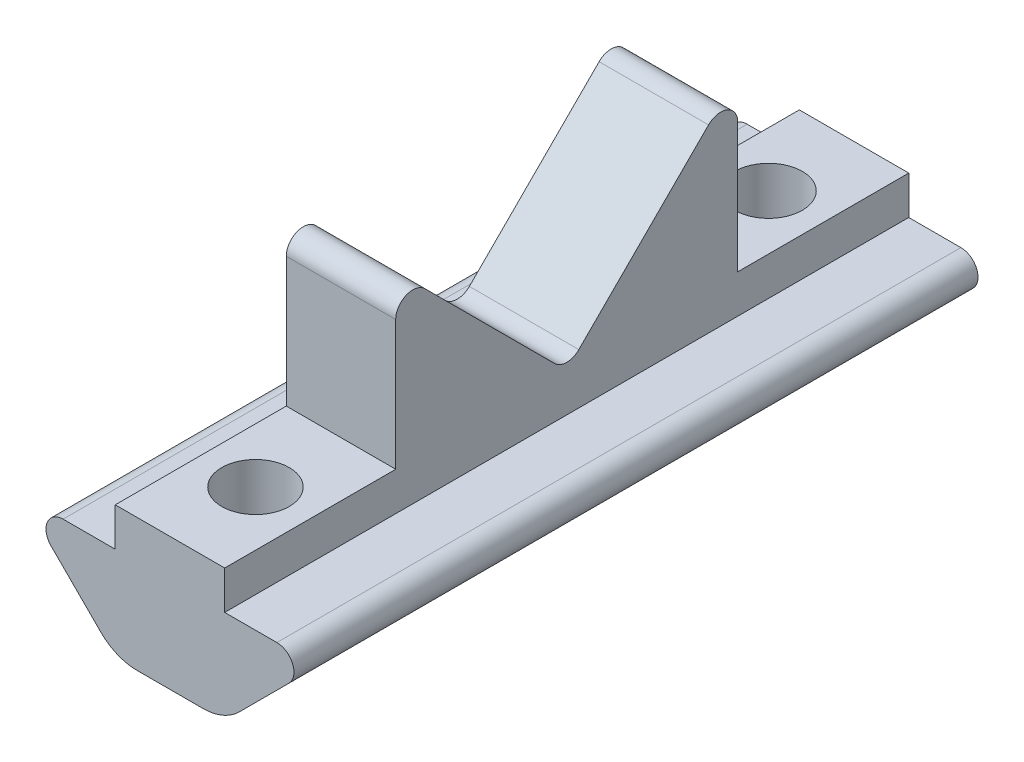
SolidWorks part; units mm, degrees
material "PETG"
ref_plane "Front Plane" through (0, 0, 0) normal (0, 0, 1) x (1, 0, 0)
ref_plane "Top Plane" through (0, 0, 0) normal (0, 1, 0) x (1, 0, 0)
ref_plane "Right Plane" through (0, 0, 0) normal (1, 0, 0) x (0, 0, -1)
sketch "Sketch2" plane through (0, 0, 0) normal (0, 0, 1) x (1, 0, 0)
  line L0 (-1.9216, 0) -> (1.9216, 0)
  line L1 (4.0429, 0.8787) -> (6.9571, 3.7929)
  line L2 (6.25, 5.5) -> (3.2, 5.5)
  line L3 (3.2, 5.5) -> (3.2, 7.75)
  line L4 (3.2, 7.75) -> (-3.2, 7.75)
  line L5 (-3.2, 7.75) -> (-3.2, 5.5)
  line L6 (-3.2, 5.5) -> (-6.25, 5.5)
  line L7 (-6.9571, 3.7929) -> (-4.0429, 0.8787)
  arc A0 (6.9571, 3.7929) -> (6.25, 5.5) centre (6.25, 4.5) ccw
  arc A1 (-6.25, 5.5) -> (-6.9571, 3.7929) centre (-6.25, 4.5) ccw
  arc A2 (1.9216, 0) -> (4.0429, 0.8787) centre (1.9216, 3) ccw
  arc A3 (-1.9216, 0) -> (-4.0429, 0.8787) centre (-1.9216, 3) cw
  point P9 (-5.5096, 8.6725)
  point P10 (10.2362, 8.9557)
  point P11 (1.8535, 9.9752)
  point P12 (0, 0)
  point P13 (-3.6405, 9.0689)
  point P14 (3.2695, 10.7115)
  point P15 (-2.3052, 0)
  point P16 (-4.7671, 0)
  point P17 (-8.1654, 5.5)
  dimension "D1" = 1
  dimension "D5" = 3
  dimension "D2" = 12.5
  dimension "D3" = 45
  dimension "D4" = 5.5
  dimension "D6" = 6.4
  dimension "D7" = 2.25
extrude "Boss-Extrude1" add sketch "Sketch2" along normal mid plane 40
sketch "Sketch3" plane through (0, 7.75, 0) normal (0, 1, 0) x (1, 0, 0)
  line L0 (0, 0) -> (50000, 0) construction
  line L1 (3.2, 20) -> (-3.2, 20) construction
  circle A0 centre (0, 15) radius 1.975
  circle A1 centre (0, -15) radius 1.975
  point P7 (0, 15)
  point P8 (0, 0)
  dimension "D1" = 5
  dimension "D2" = 3.95
extrude "Cut-Extrude1" cut sketch "Sketch3" against normal through all
sketch "Sketch4" plane through (0, 0, 0) normal (1, 0, 0) x (0, 0, -1)
  line L0 (-10, 7.75) -> (-10, 17.75)
  line L1 (-20, 7.75) -> (20, 7.75) construction
  line L2 (-10, 17.75) -> (0, 7.75)
  line L4 (-10, 7.75) -> (10, 7.75)
  line L5 (0, 0) -> (0, 50000) construction
  line L6 (-14.5437, 0) -> (14.5437, 0) construction
  line L7 (10, 7.75) -> (10, 17.75)
  line L8 (10, 17.75) -> (0, 7.75)
  point P9 (0, 0)
  dimension "D1" = 10
  dimension "D2" = 10
extrude "Boss-Extrude2" add sketch "Sketch4" along normal up to surface and the other way up to surface contours L0 L4 L2 | L7 L8 L4 up to face at (3.2, 6.625, 0) other way up to face at (-3.2, 6.625, 0)
fillet "Fillet1" radius 1 3 edges at (0, 7.75, 0) (0, 17.75, -10) (0, 17.75, 10)
